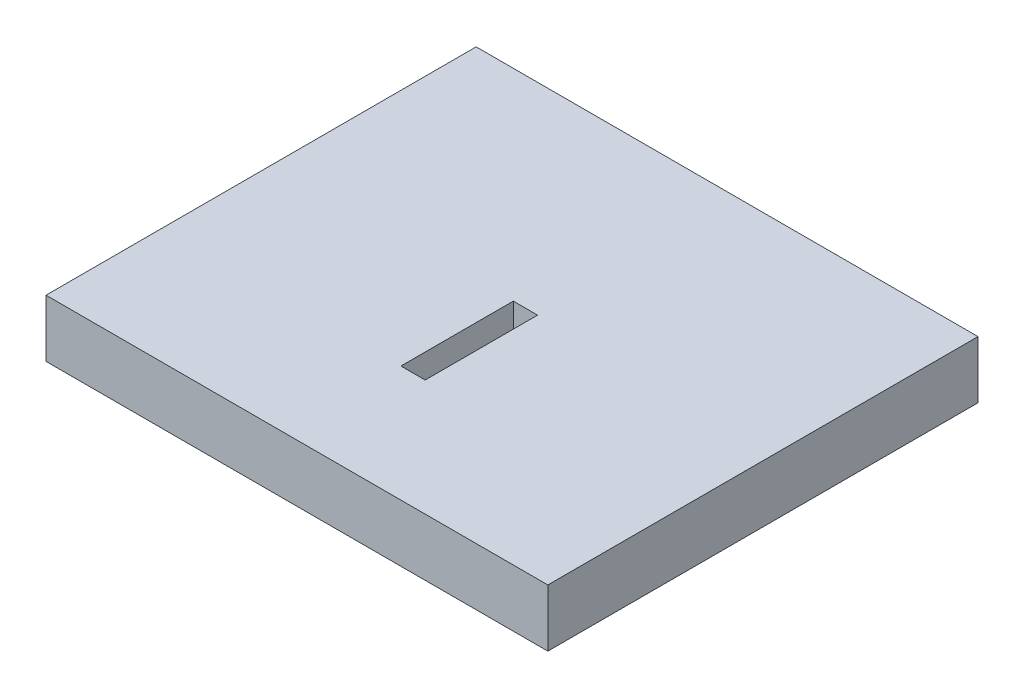
SolidWorks part; units mm, degrees
ref_plane "Front Plane" through (0, 0, 0) normal (0, 0, 1) x (1, 0, 0)
ref_plane "Top Plane" through (0, 0, 0) normal (0, 1, 0) x (1, 0, 0)
ref_plane "Right Plane" through (0, 0, 0) normal (1, 0, 0) x (0, 0, -1)
sketch "Sketch1" plane through (0, 0, 0) normal (0, 1, 0) x (1, 0, 0)
  line L1 (0, 0) -> (35, 0)
  line L2 (0, 0) -> (0, -30)
  line L3 (0, -30) -> (35, -30)
  line L4 (35, 0) -> (35, -30)
  line L5 (16.654, -14.0626) -> (18.346, -14.0626)
  line L6 (16.654, -14.0626) -> (16.654, -21.9022)
  line L7 (16.654, -21.9022) -> (18.346, -21.9022)
  line L8 (18.346, -14.0626) -> (18.346, -21.9022)
  line L9 (16.654, -14.0626) -> (18.346, -21.9022) construction
  line L10 (16.654, -21.9022) -> (18.346, -14.0626) construction
  point P5 (17.5, -17.9824)
  dimension "D1" = 35
  dimension "D2" = 30
extrude "Boss-Extrude1" add sketch "Sketch1" along normal blind 4
